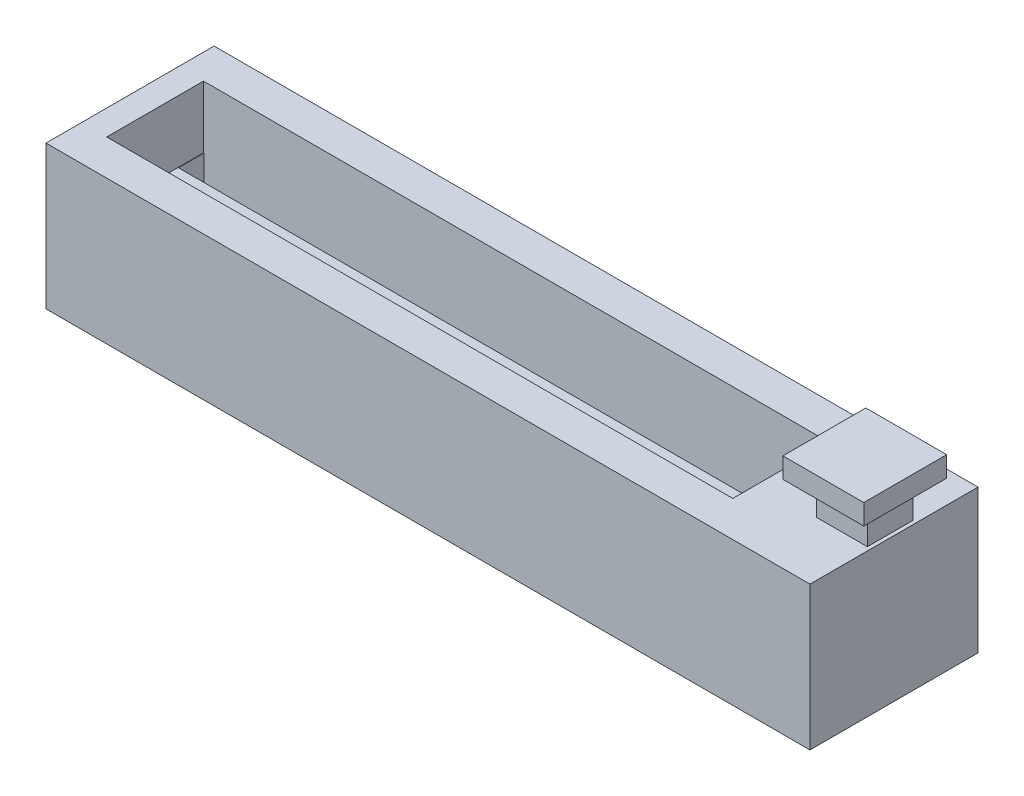
SolidWorks part; units mm, degrees
ref_plane "Front Plane" through (0, 0, 0) normal (0, 0, 1) x (1, 0, 0)
ref_plane "Top Plane" through (0, 0, 0) normal (0, 1, 0) x (1, 0, 0)
ref_plane "Right Plane" through (0, 0, 0) normal (1, 0, 0) x (0, 0, -1)
sketch3d "3DSketch1"
  line L0 (0, 0, 0) -> (66.5, 0, 0)
  line L1 (66.5, 0, 0) -> (66.5, 0, 16.5)
  line L2 (66.5, 0, 16.5) -> (0, 0, 16.5)
  line L3 (0, 0, 0) -> (0, 0, 16.5)
  line L4 (0, 0, 0) -> (0, 13, 0)
extrude "Boss-Extrude1" add sketch "3DSketch1" along direction (0, 1, 0) on the side of the normal blind 13 contours L0 L1 L2 L3
sketch3d "3DSketch2"
  line L0 (0, 0, 0) -> (0, 0, 3.5)
  line L1 (0, 0, 0) -> (0, 0, 16.5) construction
  line L2 (0, 13, 3.5) -> (0, 0, 3.5)
  line L3 (0, 0, 3.5) -> (0, 0, 13)
  line L4 (0, 13, 0) -> (0, 13, 16.5) construction
  line L5 (0, 13, 3.5) -> (0, 13, 6)
  line L6 (0, 13, 6) -> (0, 0, 6)
  line L7 (0, 0, 0) -> (66.5, 0, 0)
  line L8 (0, 0, 10.5) -> (0, 13, 10.5)
  line L9 (0, 13, 10.5) -> (0, 13, 13)
  line L10 (0, 13, 13) -> (0, 0, 13)
  line L11 (0, 0, 13) -> (0, 0, 16.5)
  line L12 (0, 0, 3.5) -> (0, 0, 6)
  line L13 (0, 0, 10.5) -> (0, 0, 13)
extrude "Cut-Extrude1" cut sketch "3DSketch2" along direction (1, 0, 0) on the side of the normal blind 66.5 contours L2 L5 L6 L12 | L13 L8 L9 L10
sketch3d "3DSketch3"
  line L1 (0, 0, 0) -> (0, 0, 16.5)
  line L2 (0, 0, 16.5) -> (66.5, 0, 16.5)
  line L3 (66.5, 0, 0) -> (66.5, 0, 16.5)
  line L5 (2.5, 0, 0) -> (0, 0, 0)
  line L7 (66.5, 0, 0) -> (64, 0, 0)
  line L8 (64, 0, 3.5) -> (64, 0, 13)
  line L9 (2.5, 0, 0) -> (64, 0, 0)
  line L10 (2.5, 0, 3.5) -> (64, 0, 3.5)
  line L11 (2.5, 0, 3.5) -> (2.5, 0, 13)
  line L12 (2.5, 0, 13) -> (64, 0, 13)
  line L13 (0, 0, 0) -> (0, 13, 0)
  line L14 (0, 0, 0) -> (0, 13, 0) construction
  line L15 (0, 13, 0) -> (66.5, 13, 0)
  line L16 (66.5, 0, 0) -> (66.5, 13, 0) construction
  line L17 (0, 13, 0) -> (66.5, 13, 0) construction
  line L18 (66.5, 13, 0) -> (66.5, 13, 16.5)
  line L19 (66.5, 13, 16.5) -> (0, 13, 16.5)
  line L20 (0, 13, 16.5) -> (0, 13, 0)
extrude "Boss-Extrude4" add sketch "3DSketch3" along direction (0, 1, 0) on the side of the normal blind 6.1 contours L15 L18 L19 L20
sketch3d "3DSketch4"
  line L0 (0, 13, 3.5) -> (0, 19.1, 3.5)
  line L1 (0, 19.1, 0) -> (2.4636, 19.1, 0)
  line L2 (0, 19.1, 0) -> (66.5, 19.1, 0) construction
  line L3 (2.4636, 19.1, 3.5) -> (63.9293, 19.1, 3.5)
  line L7 (0, 19.1, 0) -> (0, 19.1, 3.5)
  line L8 (0, 19.1, 16.5) -> (0, 19.1, 0) construction
  line L9 (63.9293, 19.1, 3.5) -> (63.9293, 19.1, 13)
  line L10 (2.4636, 19.1, 3.5) -> (2.4636, 19.1, 13)
  line L11 (2.4636, 19.1, 13) -> (63.9293, 19.1, 13)
extrude "Cut-Extrude2" cut sketch "3DSketch4" along direction (0, 1, 0) on the side against the normal blind 6.1 contours L10 L11 L9 L3
sketch3d "3DSketch5"
  line L0 (0, 13, 3.5) -> (0, 11.5355, 3.5)
  line L1 (0, 13, 3.5) -> (0, 0, 3.5) construction
  line L3 (0, 13, 6) -> (0, 0, 6) construction
  line L4 (0, 11.5355, 6) -> (0, 13, 6)
  line L5 (0, 13, 6) -> (0, 13, 3.5)
  line L6 (0, 13, 6) -> (0, 13, 10.5)
  line L7 (0, 13, 10.5) -> (0, 11.5355, 10.5)
  line L8 (0, 0, 10.5) -> (0, 13, 10.5) construction
  line L10 (0, 13, 13) -> (0, 0, 13) construction
  line L11 (0, 11.5355, 13) -> (0, 13, 13)
  line L12 (0, 13, 13) -> (0, 13, 10.5)
  line L13 (0, 11.5355, 3.5) -> (0, 9.0355, 3.5)
  line L14 (0, 9.0355, 3.5) -> (0, 9.0355, 6)
  line L15 (0, 9.0355, 6) -> (0, 11.5355, 6)
  line L16 (0, 11.5355, 10.5) -> (0, 9.0355, 10.5)
  line L17 (0, 9.0355, 10.5) -> (0, 9.0355, 13)
  line L18 (0, 9.0355, 13) -> (0, 11.5355, 13)
extrude "Boss-Extrude6" add sketch "3DSketch5" along a picked direction on the side against the normal blind 2.5 contours L5 L0 L13 L14 L15 L4 | L7 L16 L17 L18 L11 L12
sketch3d "3DSketch6"
  line L0 (66.5, 0, 13) -> (66.5, 0, 10.5)
  line L1 (66.5, 0, 10.5) -> (66.5, 13, 10.5)
  line L2 (66.5, 13, 10.5) -> (66.5, 13, 13)
  line L3 (66.5, 13, 13) -> (66.5, 0, 13)
  line L4 (66.5, 13, 6) -> (66.5, 0, 6)
  line L5 (66.5, 0, 6) -> (66.5, 0, 3.5)
  line L6 (66.5, 0, 3.5) -> (66.5, 13, 3.5)
  line L7 (66.5, 13, 3.5) -> (66.5, 13, 6)
extrude "Boss-Extrude7" add sketch "3DSketch6" along a picked direction on the side of the normal blind 2.5 contours L0 L1 L2 L3 | L4 L5 L6 L7
sketch3d "3DSketch7"
  line L0 (66.5, 0, 0) -> (86.5, 0, 0)
  line L1 (86.5, 0, 0) -> (86.5, 0, 16.5)
  line L2 (86.5, 0, 16.5) -> (66.5, 0, 16.5)
  line L3 (66.5, 0, 0) -> (66.5, 0, 16.5)
extrude "Boss-Extrude8" add sketch "3DSketch7" along a picked direction on the side of the normal blind 19.1 contours L2 L3 L0 L1
sketch3d "3DSketch8"
  line L0 (76.1289, 13, 6) -> (76.1289, 13, 10.5)
  line L3 (86.4293, 13, 6) -> (86.4293, 13, 10.5)
  line L4 (86.4293, 13, 10.5) -> (63.9293, 13, 10.5)
  line L7 (79.6376, 13, 10.5) -> (79.6376, 13, 6)
  line L10 (72.1098, 13, 10.5) -> (79.6376, 13, 10.5)
  line L11 (79.6376, 13, 6) -> (76.1289, 13, 6)
  line L12 (76.1289, 13, 10.5) -> (79.6376, 13, 10.5)
extrude "Boss-Extrude12" add sketch "3DSketch8" along a picked direction on the side of the normal blind 9.5 contours L7 L11 L0 L12
sketch3d "3DSketch9"
  line L0 (76.1289, 22.5, 8.25) -> (77.8789, 22.5, 8.25)
  line L1 (76.1289, 22.5, 6) -> (76.1289, 22.5, 10.5) construction
  line L3 (75.3458, 22.5, 11.7647) -> (75.3458, 22.5, 4.7353)
  line L4 (75.3458, 22.5, 11.7647) -> (80.412, 22.5, 11.7647)
  line L5 (80.412, 22.5, 11.7647) -> (80.412, 22.5, 4.7353)
  line L6 (75.3458, 22.5, 4.7353) -> (80.412, 22.5, 4.7353)
  line L7 (75.3458, 22.5, 11.7647) -> (80.412, 22.5, 4.7353) construction
  line L8 (80.412, 22.5, 11.7647) -> (75.3458, 22.5, 4.7353) construction
extrude "Boss-Extrude13" add sketch "3DSketch9" along a picked direction on the side of the normal blind 2.5 contours L5 L6 L3 L4
sketch3d "3DSketch11"
  line L2 (0, 0, 0) -> (0, 0, 16.5)
  line L3 (0, 0, 16.5) -> (86.5, 0, 16.5)
  line L4 (86.5, 0, 16.5) -> (86.5, 0, 0)
  line L5 (86.5, 0, 0) -> (0, 0, 0)
extrude "Cut-Extrude4" cut sketch "3DSketch11" along a picked direction on the side against the normal blind 5
sketch3d "3DSketch12"
  line L0 (86.5, 5, 0) -> (86.5, 5, 16.5)
  line L1 (86.5, 5, 16.5) -> (86.5, 19.1, 16.5)
  line L2 (86.5, 19.1, 16.5) -> (86.5, 19.1, 0)
  line L3 (86.5, 19.1, 0) -> (86.5, 5, 0)
extrude "Cut-Extrude5" cut sketch "3DSketch12" along a picked direction on the side against the normal blind 6.5
sketch3d "3DSketch13"
  line L0 (80.412, 25, 11.7647) -> (80.412, 22.5, 11.7647)
  line L1 (79.6376, 22.5, 10.5) -> (79.6376, 19.1, 10.5)
  line L2 (79.6376, 22.5, 10.5) -> (79.6376, 22.5, 6)
  line L3 (80.412, 22.5, 11.7647) -> (80.412, 22.5, 10.503)
  line L4 (79.6376, 22.5, 6) -> (79.6376, 22.5, 4.7454)
  line L5 (79.6376, 22.5, 4.7454) -> (79.6376, 24.9715, 4.7454)
  line L6 (80.412, 25, 11.7647) -> (80.412, 25, 4.7353)
  line L7 (80.412, 25, 11.7647) -> (80.412, 25, 4.7353) construction
  line L8 (79.6376, 22.5, 6) -> (79.6376, 19.1, 6)
  line L9 (79.6376, 19.1, 6) -> (79.6376, 19.1, 10.5)
extrude "Boss-Extrude14" add sketch "3DSketch13" along a picked direction on the side of the normal blind 10 contours L2 L1 L9 L8
sketch3d "3DSketch14"
  line L0 (80.412, 22.5, 4.7353) -> (80.412, 25, 4.7353)
  line L1 (80.412, 25, 4.7353) -> (80.412, 25, 11.7647)
  line L2 (80.412, 25, 11.7647) -> (80.412, 22.5, 11.7647)
  line L3 (80.412, 22.5, 11.7647) -> (80.412, 22.5, 4.7353)
extrude "Cut-Extrude7" cut sketch "3DSketch14" along a picked direction on the side of the normal blind 13
sketch3d "3DSketch15"
  line L0 (79.6376, 22.5, 10.5) -> (79.6376, 19.1, 10.5)
  line L1 (79.6376, 19.1, 10.5) -> (79.6376, 19.1, 6)
  line L2 (79.6376, 19.1, 6) -> (79.6376, 22.5, 6)
  line L3 (79.6376, 22.5, 6) -> (79.6376, 22.5, 10.5)
extrude "Cut-Extrude8" cut sketch "3DSketch15" along a picked direction on the side of the normal blind 5
sketch3d "3DSketch16"
  line L0 (80, 19.1, 0) -> (80, 19.1, 16.5)
  line L1 (80, 19.1, 16.5) -> (80, 5, 16.5)
  line L2 (80, 5, 16.5) -> (80, 5, 0)
  line L3 (80, 5, 0) -> (80, 19.1, 0)
extrude "Cut-Extrude9" cut sketch "3DSketch16" along a picked direction on the side of the normal blind 5
sketch3d "3DSketch17"
  line L1 (74.6376, 22.5, 10.5) -> (74.6376, 22.5, 6)
  line L5 (72.1376, 22.5, 8.25) -> (74.6376, 22.5, 8.25)
  line L6 (68.1687, 22.5, 12.3202) -> (68.1687, 22.5, 4.1798)
  line L7 (68.1687, 22.5, 12.3202) -> (76.1066, 22.5, 12.3202)
  line L8 (76.1066, 22.5, 12.3202) -> (76.1066, 22.5, 4.1798)
  line L9 (68.1687, 22.5, 4.1798) -> (76.1066, 22.5, 4.1798)
  line L10 (68.1687, 22.5, 12.3202) -> (76.1066, 22.5, 4.1798) construction
  line L11 (76.1066, 22.5, 12.3202) -> (68.1687, 22.5, 4.1798) construction
extrude "Boss-Extrude15" add sketch "3DSketch17" along a picked direction on the side against the normal blind 2 contours L8 L9 L6 L7
sketch3d "3DSketch18"
  line L0 (0, 19.1, 16.5) -> (0, 19.1, 0) construction
  line L3 (0, 19.1, 8.25) -> (-27.672, 19.1, 8.25)
  line L4 (-23.8189, 5.0132, -12.5578) -> (-23.8189, 5.0132, 7.7422) construction
  line L5 (-23.8189, -13.4868, 7.7422) -> (-23.8189, 5.0132, 7.7422)
  line L6 (-23.8189, -13.4868, 6.9422) -> (-23.8189, -13.4868, 7.7422) construction
  line L7 (-23.8189, -13.4868, 6.9422) -> (-23.8189, -13.4868, 7.7422)
  line L9 (0, 5, 6) -> (0, 5, 10.5) construction
  line L10 (0, 5, 8.25) -> (0, 5, 8.75)
  line L11 (0, 5, 8.25) -> (0, 5, 7.75)
  line L12 (0, 5, 7.75) -> (-23.8189, 5.0132, 7.7422)
  line L13 (-23.8189, 5.0132, 7.7422) -> (-23.8189, 5.0132, 8.7422)
  line L14 (-23.8189, 5.0132, 8.7422) -> (0, 5, 8.75)
  dimension "D1" = 27.6727
